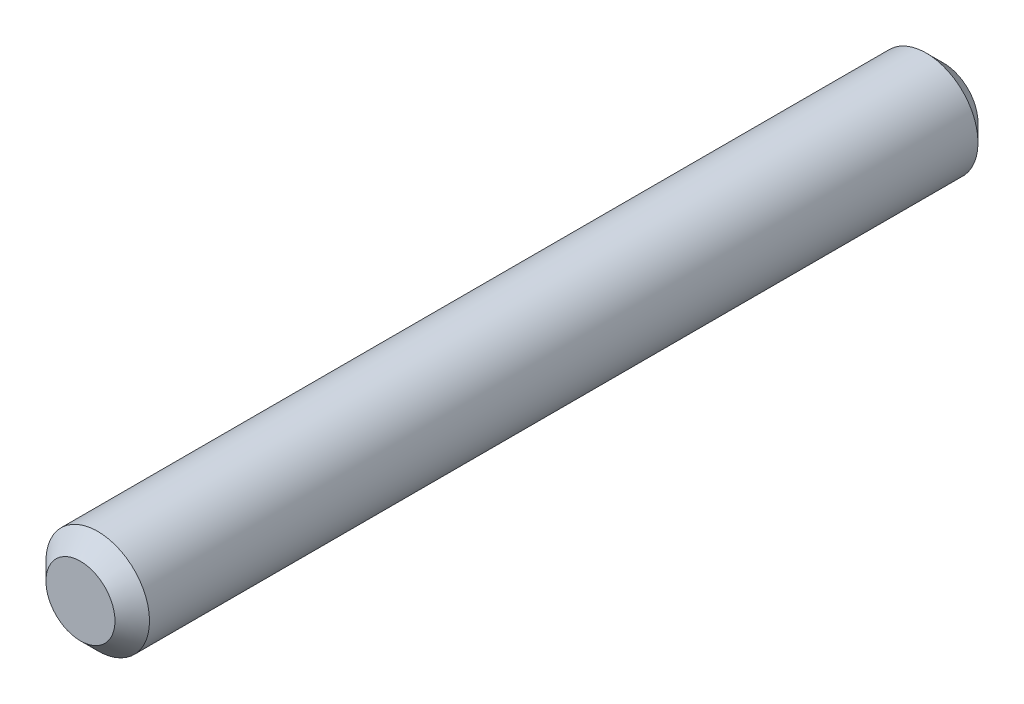
SolidWorks part; units mm, degrees
material "Stainless Steel (ferritic)"
ref_plane "Front Plane" through (0, 0, 0) normal (0, 0, 1) x (1, 0, 0)
ref_plane "Top Plane" through (0, 0, 0) normal (0, 1, 0) x (1, 0, 0)
ref_plane "Right Plane" through (0, 0, 0) normal (1, 0, 0) x (0, 0, -1)
sketch "Sketch1" plane through (0, 0, 0) normal (0, 0, 1) x (1, 0, 0)
  circle A0 centre (0, 0) radius 1.5
  dimension "D1" = 3
extrude "Boss-Extrude1" add sketch "Sketch1" along normal blind 25
chamfer "Chamfer1" distance 0.5 angle 45 2 edges at (1.5, 0, 0) (1.5, 0, 25)
